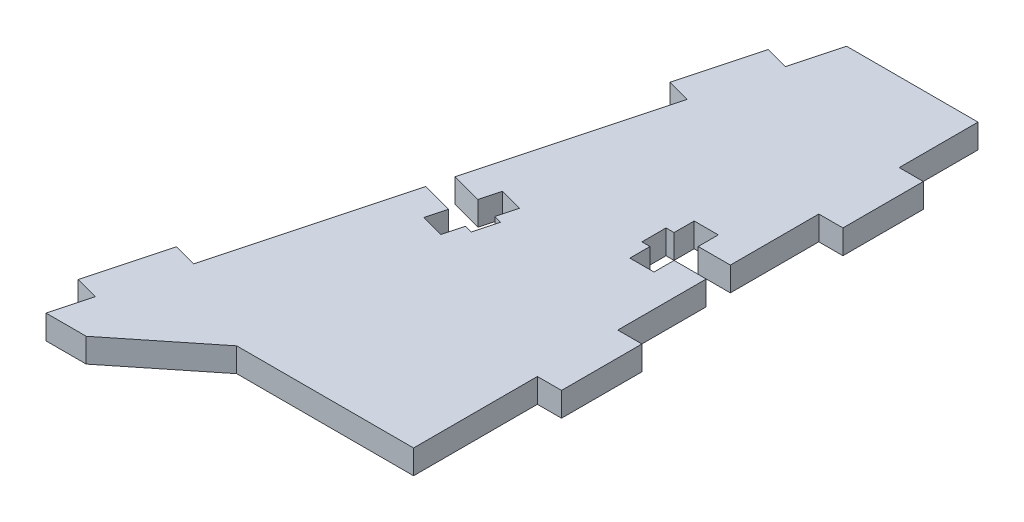
SolidWorks part; units mm, degrees
material "Balsa"
ref_plane "Alzado" through (0, 0, 0) normal (0, 0, 1) x (1, 0, 0)
ref_plane "Planta" through (0, 0, 0) normal (0, 1, 0) x (1, 0, 0)
ref_plane "Vista lateral" through (0, 0, 0) normal (1, 0, 0) x (0, 0, -1)
sketch "Croquis1" plane through (0, 0, 0) normal (0, 1, 0) x (1, 0, 0)
  line L0 (33650.1396, 12767.283) -> (33650.1396, 12775.0553)
  line L1 (33650.1396, 12775.3286) -> (33650.1396, 12777.283)
  line L2 (33647.1396, 12767.283) -> (33650.1396, 12767.283)
  line L3 (33643.1396, 12756.283) -> (33647.1396, 12756.283)
  line L4 (33643.1396, 12758.783) -> (33643.1396, 12756.283)
  line L5 (33640.1396, 12758.783) -> (33643.1396, 12758.783)
  line L6 (33640.1396, 12756.283) -> (33640.1396, 12758.783)
  line L7 (33639.1396, 12756.283) -> (33640.1396, 12756.283)
  line L8 (33639.1396, 12753.283) -> (33639.1396, 12756.283)
  line L9 (33640.1396, 12753.283) -> (33639.1396, 12753.283)
  line L10 (33640.1396, 12750.783) -> (33640.1396, 12753.283)
  line L11 (33643.1396, 12750.783) -> (33640.1396, 12750.783)
  line L12 (33643.1396, 12753.283) -> (33643.1396, 12750.783)
  line L13 (33647.1396, 12753.283) -> (33643.1396, 12753.283)
  line L14 (33647.1396, 12742.283) -> (33647.1396, 12746.183)
  line L15 (33650.1396, 12742.283) -> (33647.1396, 12742.283)
  line L16 (33650.1396, 12732.283) -> (33650.1396, 12737.0814)
  line L17 (33650.1396, 12737.3526) -> (33650.1396, 12742.283)
  line L18 (33647.1396, 12732.283) -> (33650.1396, 12732.283)
  line L19 (33647.1396, 12716.883) -> (33647.1396, 12732.283)
  line L20 (33625.1396, 12716.883) -> (33636.1401, 12716.883)
  line L21 (33636.4303, 12716.883) -> (33647.1396, 12716.883)
  line L22 (33614.7488, 12708.5571) -> (33625.1396, 12716.883)
  line L23 (33609.7488, 12708.5571) -> (33614.7488, 12708.5571)
  line L24 (33611.0429, 12713.3867) -> (33609.7488, 12708.5571)
  line L25 (33608.1451, 12714.1632) -> (33611.0429, 12713.3867)
  line L26 (33610.7333, 12723.8224) -> (33608.1451, 12714.1632)
  line L27 (33613.6311, 12723.046) -> (33610.7333, 12723.8224)
  line L28 (33619.725, 12745.7887) -> (33617.5149, 12737.5408)
  line L29 (33617.4371, 12737.2504) -> (33613.6311, 12723.046)
  line L30 (33623.5887, 12744.7534) -> (33619.725, 12745.7887)
  line L31 (33622.9416, 12742.3386) -> (33623.5887, 12744.7534)
  line L32 (33625.8394, 12741.5622) -> (33622.9416, 12742.3386)
  line L33 (33626.4865, 12743.977) -> (33625.8394, 12741.5622)
  line L34 (33627.4524, 12743.7181) -> (33626.4865, 12743.977)
  line L35 (33628.2288, 12746.6159) -> (33627.4524, 12743.7181)
  line L36 (33627.2629, 12746.8747) -> (33628.2288, 12746.6159)
  line L37 (33627.91, 12749.2896) -> (33627.2629, 12746.8747)
  line L38 (33625.0122, 12750.066) -> (33627.91, 12749.2896)
  line L39 (33624.3651, 12747.6512) -> (33625.0122, 12750.066)
  line L40 (33620.5014, 12748.6865) -> (33624.3651, 12747.6512)
  line L41 (33626.5958, 12771.4309) -> (33620.5014, 12748.6865)
  line L42 (33623.698, 12772.2074) -> (33626.5958, 12771.4309)
  line L43 (33626.2862, 12781.8666) -> (33624.5738, 12775.476)
  line L44 (33624.4966, 12775.1879) -> (33623.698, 12772.2074)
  line L45 (33629.184, 12781.0902) -> (33626.2862, 12781.8666)
  line L46 (33630.7897, 12787.0829) -> (33629.184, 12781.0902)
  line L47 (33647.1396, 12787.0829) -> (33635.9458, 12787.0829)
  line L48 (33635.6718, 12787.0829) -> (33630.7897, 12787.0829)
  line L49 (33647.1396, 12777.283) -> (33647.1396, 12787.0829)
  line L50 (33650.1396, 12777.283) -> (33647.1396, 12777.283)
  line L51 (33647.1396, 12746.183) -> (33647.1396, 12749.183)
  line L52 (33647.1396, 12749.183) -> (33647.1396, 12753.283)
  line L53 (33647.1396, 12756.283) -> (33647.1396, 12767.283)
  line L54 (33635.6718, 12787.0829) -> (33635.9458, 12787.0829)
  line L55 (33624.4966, 12775.1879) -> (33624.5738, 12775.476)
  line L56 (33617.4371, 12737.2504) -> (33617.5149, 12737.5408)
  line L57 (33636.1401, 12716.883) -> (33636.4303, 12716.883)
  line L58 (33650.1396, 12737.0814) -> (33650.1396, 12737.3526)
  line L59 (33650.1396, 12775.0553) -> (33650.1396, 12775.3286)
  dimension "D1" = 70.1999
extrude "Saliente-Extruir1" add sketch "Croquis1" along normal blind 3
